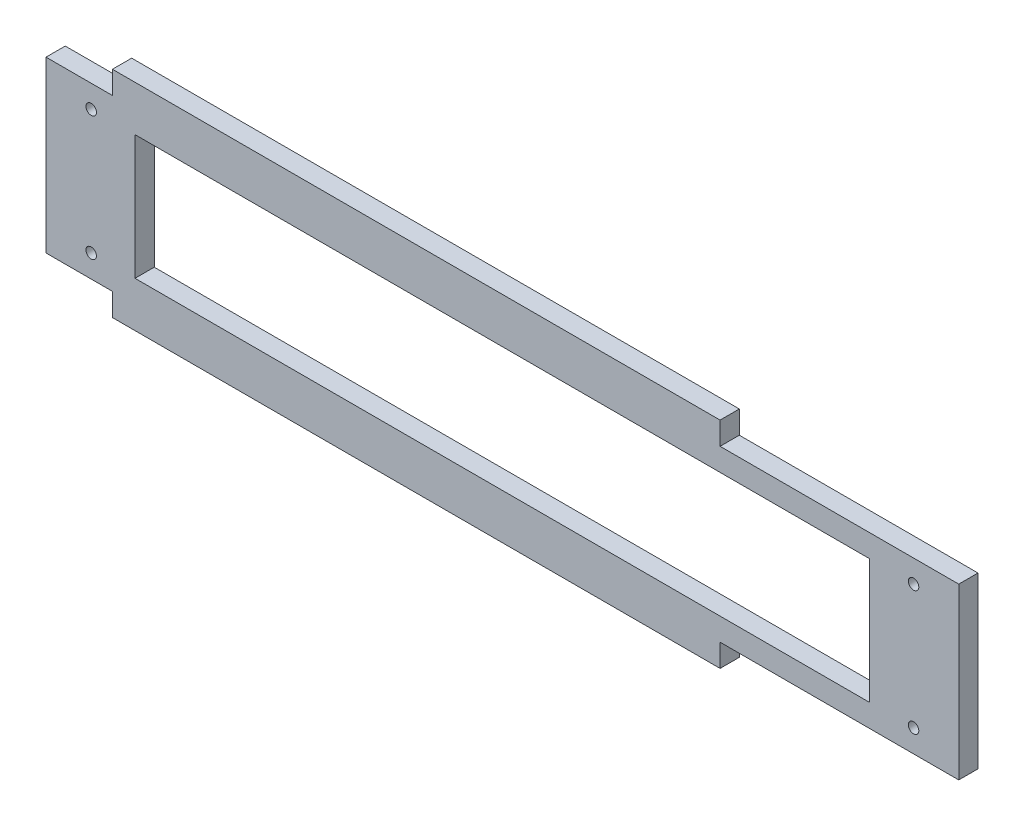
SolidWorks part; units mm, degrees
ref_plane "Front Plane" through (0, 0, 0) normal (0, 0, 1) x (1, 0, 0)
ref_plane "Top Plane" through (0, 0, 0) normal (0, 1, 0) x (1, 0, 0)
ref_plane "Right Plane" through (0, 0, 0) normal (1, 0, 0) x (0, 0, -1)
sketch "Sketch1" plane through (0, 0, 0) normal (0, 0, 1) x (1, 0, 0)
  line L0 (-109.601, 23.8379) -> (-109.601, -23.8379)
  line L1 (128.27, -23.8379) -> (-128.27, -23.8379)
  line L2 (128.27, -23.8379) -> (128.27, 23.8379)
  line L3 (128.27, 23.8379) -> (-128.27, 23.8379)
  line L4 (-128.27, -23.8379) -> (-128.27, 23.8379)
  line L5 (128.27, -23.8379) -> (-128.27, 23.8379) construction
  line L6 (128.27, 23.8379) -> (-128.27, -23.8379) construction
  line L7 (121.539, 23.8379) -> (121.539, -23.8379)
  line L8 (61.191, 23.8379) -> (61.191, -23.8379)
  line L10 (-109.601, -30.226) -> (61.191, -30.226)
  line L11 (-109.601, -30.226) -> (-109.601, 30.226)
  line L12 (-109.601, 30.226) -> (61.191, 30.226)
  line L13 (61.191, -30.226) -> (61.191, 30.226)
  line L14 (-103.251, 17.4879) -> (103.251, 17.4879)
  line L15 (-103.251, 17.4879) -> (-103.251, -17.4879)
  line L16 (-103.251, -17.4879) -> (103.251, -17.4879)
  line L17 (103.251, 17.4879) -> (103.251, -17.4879)
  line L18 (-103.251, 17.4879) -> (103.251, -17.4879) construction
  line L19 (-103.251, -17.4879) -> (103.251, 17.4879) construction
  circle A0 centre (-115.57, 17.4879) radius 1.4732
  circle A1 centre (-115.57, -17.4879) radius 1.4732
  circle A2 centre (115.57, 17.4879) radius 1.4732
  circle A3 centre (115.57, -17.4879) radius 1.4732
  point P0 (0, 0)
  point P14 (-53.1429, 7.6539)
  point P15 (-53.1429, 7.6539)
  point P26 (0, 0)
  dimension "D1" = 2.9464
  dimension "D2" = 34.9758
  dimension "D3" = 0
  dimension "D4" = 34.9758
  dimension "D5" = 6.35
  dimension "D6" = 0
  dimension "D7" = 6.35
  dimension "D8" = 12.7
  dimension "D9" = 12.7
  dimension "D10" = 0
  dimension "D11" = 5.969
  dimension "D12" = 5.969
  dimension "D13" = 54.379
  dimension "D14" = 30.226
  dimension "D15" = 30.226
  dimension "D16" = 231.14
  dimension "D17" = 0
  dimension "D18" = 0
  dimension "D19" = 6.35
  dimension "D20" = 6.35
  dimension "D21" = 6.35
extrude "Boss-Extrude1" add sketch "Sketch1" along normal blind 5.4102 contours L4 L1 L0 L3 A1 A0 | L8 L3 L0 L1 | L3 L13 L12 L11 | L10 L13 L1 L11 | L3 L8 L1 L7 A3 A2 | L3 L7 L1 L2
